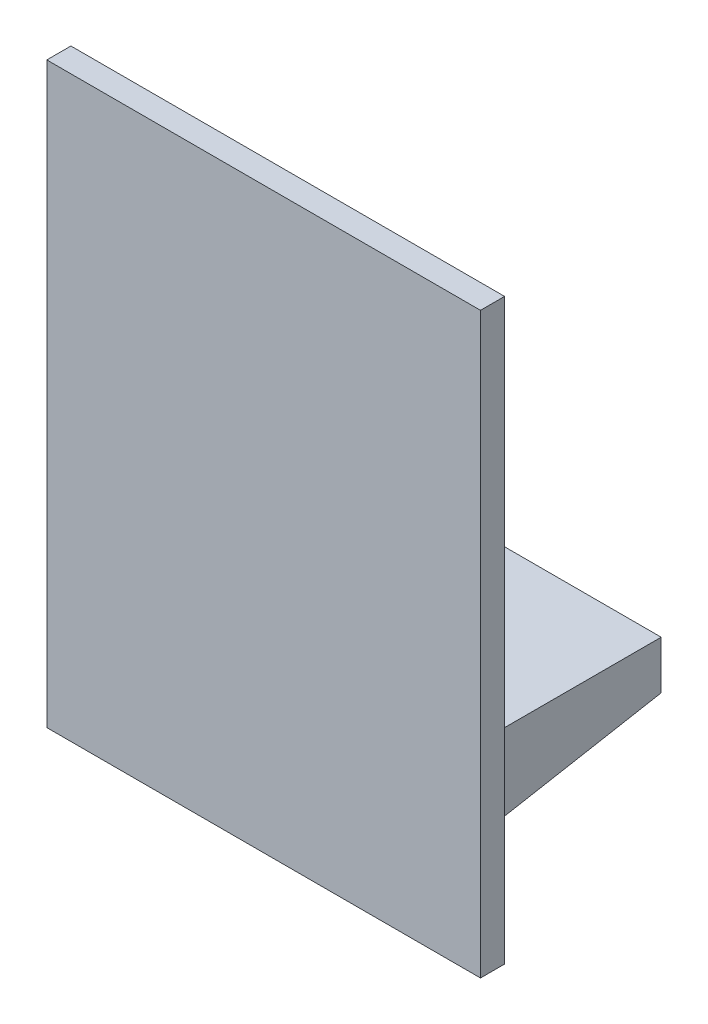
SolidWorks part; units mm, degrees
ref_plane "Front Plane" through (0, 0, 0) normal (0, 0, 1) x (1, 0, 0)
ref_plane "Top Plane" through (0, 0, 0) normal (0, 1, 0) x (1, 0, 0)
ref_plane "Right Plane" through (0, 0, 0) normal (1, 0, 0) x (0, 0, -1)
sketch "Esboço1" plane through (0, 0, 0) normal (0, 0, 1) x (1, 0, 0)
  line L6 (-22.5, -5) -> (22.5, -5)
  line L7 (-22.5, -5) -> (-22.5, 5)
  line L8 (-22.5, 5) -> (22.5, 5)
  line L9 (22.5, -5) -> (22.5, 5)
  line L10 (-22.5, -5) -> (22.5, 5) construction
  line L11 (-22.5, 5) -> (22.5, -5) construction
  point P0 (0, 0)
  dimension "D1" = 45
  dimension "D2" = 10
extrude "Ressalto-extrusão1" add sketch "Esboço1" along normal blind 55
sketch "Esboço2" plane through (0, 5, 0) normal (0, 1, 0) x (1, 0, 0)
  line L1 (45, -55) -> (-45, -55)
  line L2 (45, -55) -> (45, -60)
  line L3 (45, -60) -> (-45, -60)
  line L4 (-45, -55) -> (-45, -60)
  line L5 (45, -55) -> (-45, -60) construction
  line L6 (45, -60) -> (-45, -55) construction
  line L7 (22.5, -55) -> (-22.5, -55) construction
  point P0 (0, -57.5)
  point P5 (0, 0)
  point P7 (0, 0)
  point P9 (0, 0)
  dimension "D1" = 90
  dimension "D2" = 5
extrude "Ressalto-extrusão2" add sketch "Esboço2" along normal blind 100 and the other way blind 20
sketch "Esboço5" plane through (22.5, 0, 0) normal (1, 0, 0) x (0, 0, -1)
  line L0 (-55, -5) -> (0, -5)
  line L1 (-55, -5) -> (0, -5) construction
  line L2 (0, -5) -> (0, 5) construction
  line L3 (0, -5) -> (-55, -15)
  line L4 (-55, -15) -> (-55, -5)
  point P7 (0, 0)
extrude "Ressalto-extrusão3" add sketch "Esboço5" against normal blind 5
mirror "Espelhar1" about plane through (0, 0, 0) normal (1, 0, 0) of "Ressalto-extrusão3"
fillet "Filete1" radius 20 3 edges at (0, 5, 55) (22.5, -5, 55) (-22.5, -5, 55)
sketch "Esboço6" plane through (0, 0, 0) normal (0, 0, -1) x (-1, 0, 0)
  line L0 (17.3267, 0) -> (-17.6733, 0) construction
  circle A0 centre (-17.6733, 0) radius 1.5
  circle A1 centre (17.3267, 0) radius 1.5
  dimension "D1" = 3
  dimension "D2" = 3
  dimension "D3" = 35
extrude "Corte-extrusão1" cut sketch "Esboço6" against normal blind 10
